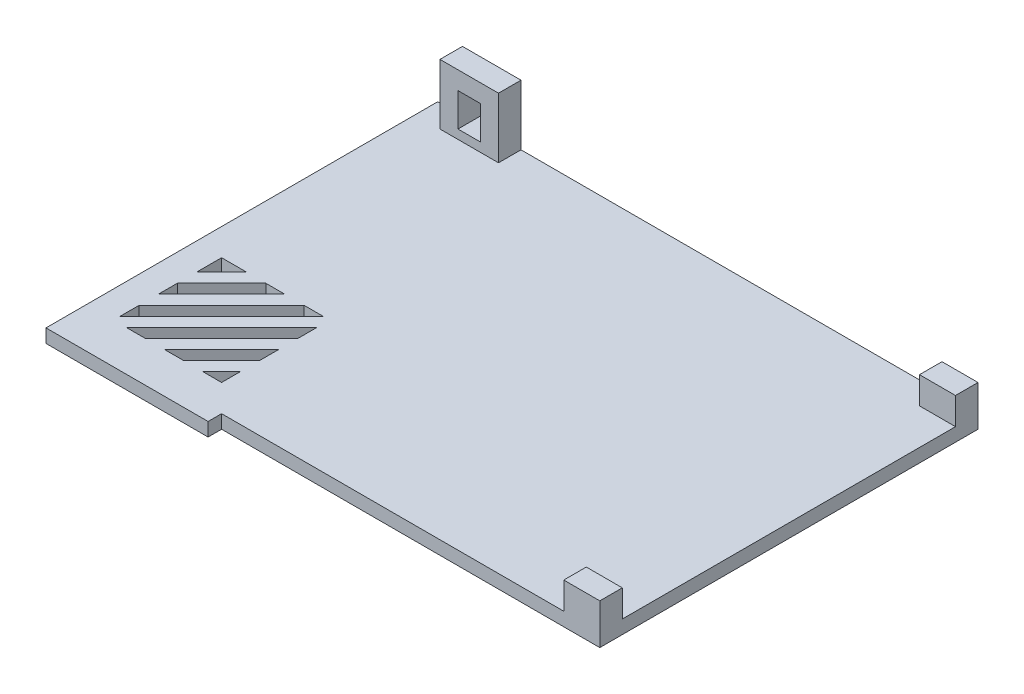
SolidWorks part; units mm, degrees
ref_plane "Спереди" through (0, 0, 0) normal (0, 0, 1) x (1, 0, 0)
ref_plane "Сверху" through (0, 0, 0) normal (0, 1, 0) x (1, 0, 0)
ref_plane "Справа" through (0, 0, 0) normal (1, 0, 0) x (0, 0, -1)
sketch "Эскиз1" plane through (0, 0, 0) normal (0, 1, 0) x (1, 0, 0)
  line L0 (0, 0) -> (0, 42) construction
  line L1 (0, 42) -> (-60, 42)
  line L2 (0, 42) -> (0, 0)
  line L3 (0, 0) -> (-60, 0)
  line L4 (-60, 42) -> (-60, 0)
  line L5 (-60, 0) -> (0, 0) construction
extrude "Бобышка-Вытянуть1" add sketch "Эскиз1" along normal blind 1.5
sketch "Эскиз2" plane through (0, 0, 0) normal (0, 1, 0) x (1, 0, 0)
  line L1 (-42, -1.5) -> (-60, -1.5)
  line L2 (-42, -1.5) -> (-42, 0)
  line L3 (-42, 0) -> (-60, 0)
  line L4 (-60, -1.5) -> (-60, 0)
extrude "Бобышка-Вытянуть2" add sketch "Эскиз2" along normal through all
sketch "Эскиз3" plane through (0, 0, 0) normal (0, 1, 0) x (1, 0, 0)
  line L0 (-51, 23.4551) -> (-51, 15) construction
  line L1 (-57, 3) -> (-45, 3)
  line L2 (-57, 3) -> (-57, 15)
  line L3 (-57, 15) -> (-45, 15)
  line L4 (-45, 3) -> (-45, 15)
  line L5 (-58, 23.4551) -> (-44, 23.4551) construction
  line L6 (-42, 0) -> (-60, 0) construction
  line L7 (-60, 42) -> (-60, -1.5) construction
  dimension "D1" = 12
  dimension "D2" = 12
  dimension "D3" = 3
extrude "Вырез-Вытянуть1" cut sketch "Эскиз3" along normal through all contours L4 L3 L2 L1
sketch "Эскиз4" plane through (0, 0, 0) normal (0, 1, 0) x (1, 0, 0)
  line L10 (-51.2426, 1) -> (-43, 9.2426)
  line L11 (-55.4853, 1) -> (-43, 13.4853)
  line L12 (-59, 1.7279) -> (-43, 17.7279)
  line L13 (-59, 5.9706) -> (-43, 21.9706)
  line L14 (-43, 17) -> (-59, 17)
  line L15 (-43, 1) -> (-43, 17)
  line L16 (-59, 17) -> (-59, 1)
  line L17 (-59, 1) -> (-43, 1)
  line L18 (-43, 17) -> (-59, 17) construction
  line L19 (-43, 1) -> (-43, 17) construction
  line L20 (-59, 17) -> (-59, 1) construction
  line L21 (-59, 1) -> (-43, 1) construction
  line L22 (-47.1213, 5.1213) -> (-49.2426, 7.2426) construction
  line L23 (-47.1213, 5.1213) -> (-45, 3) construction
  line L24 (-49.2426, 7.2426) -> (-51.364, 9.364) construction
  line L25 (-51, 9.7279) -> (-53.1213, 11.8492) construction
  line L26 (-59, 10.2132) -> (-52.2132, 17)
  line L27 (-59, 14.4558) -> (-56.4558, 17) construction
  line L28 (-51, 13.9706) -> (-53.1213, 16.0919) construction
  line L29 (-55.6066, 13.6066) -> (-57.7279, 15.7279) construction
  point P12 (-45, 3)
  dimension "D2" = 45
  dimension "D3" = 3
  dimension "D1" = 2
extrude "Вытянуть-Тонкостенный1" add sketch "Эскиз4" along normal through all thin
sketch "Эскиз5" plane through (0, 0, -42) normal (0, 0, -1) x (-1, 0, 0)
  line L0 (0, 1.5) -> (60, 1.5) construction
  line L1 (50.75, 1.5) -> (57.25, 1.5)
  line L2 (50.75, 1.5) -> (50.75, 8.1981)
  line L3 (50.75, 8.1981) -> (57.25, 8.1981)
  line L4 (57.25, 1.5) -> (57.25, 8.1981)
  line L5 (54, 8.1981) -> (54, 1.5) construction
  line L6 (52.75, 6.1981) -> (55.25, 6.1981)
  line L7 (52.75, 6.1981) -> (52.75, 2.5)
  line L8 (52.75, 2.5) -> (55.25, 2.5)
  line L9 (55.25, 6.1981) -> (55.25, 2.5)
  line L10 (52.75, 4.349) -> (55.25, 4.349) construction
  line L11 (53, 3) -> (55, 3) construction
  line L12 (53, 6.0981) -> (55, 6.0981) construction
  point P14 (54, 4.349)
  point P15 (54, 3)
  point P16 (54, 6.0981)
  dimension "D1" = 2.5
  dimension "D2" = 1
  dimension "D3" = 0.1
  dimension "D4" = 2
  dimension "D5" = 2
extrude "Бобышка-Вытянуть3" add sketch "Эскиз5" against normal blind 2.5
sketch "Эскиз7" plane through (0, 1.5, 0) normal (0, 1, 0) x (1, 0, 0)
  line L1 (0, 0) -> (-4, 0)
  line L2 (0, 0) -> (0, 2.5)
  line L3 (0, 2.5) -> (-4, 2.5)
  line L4 (-4, 0) -> (-4, 2.5)
  line L5 (0, 42) -> (-4, 42)
  line L6 (0, 42) -> (0, 39.5)
  line L7 (0, 39.5) -> (-4, 39.5)
  line L8 (-4, 42) -> (-4, 39.5)
  dimension "D1" = 2.5
  dimension "D2" = 4
extrude "Бобышка-Вытянуть4" add sketch "Эскиз7" along normal blind 3
